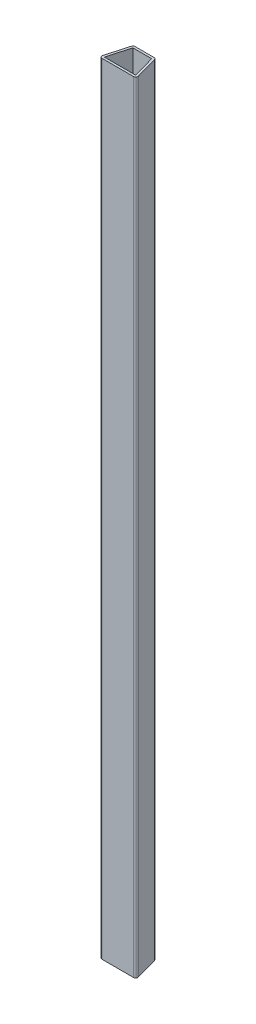
SolidWorks part; units mm, degrees
ref_plane "Front Plane" through (0, 0, 0) normal (0, 0, 1) x (1, 0, 0)
ref_plane "Top Plane" through (0, 0, 0) normal (0, 1, 0) x (1, 0, 0)
ref_plane "Right Plane" through (0, 0, 0) normal (1, 0, 0) x (0, 0, -1)
sketch "Sketch1" plane through (0, 0, 0) normal (0, 1, 0) x (1, 0, 0)
  line L8 (-7.0399, -6) -> (7.0399, -6)
  line L9 (5.19, 5.2707) -> (8.0025, -4.7293)
  line L10 (-4.2274, 6) -> (4.2274, 6)
  line L11 (-5.19, 5.2707) -> (-8.0025, -4.7293)
  line L12 (-7.0399, -5) -> (7.0399, -5)
  line L13 (4.2274, 5) -> (7.0399, -5)
  line L14 (-4.2274, 5) -> (4.2274, 5)
  line L15 (-4.2274, 5) -> (-7.0399, -5)
  arc A8 (5.19, 5.2707) -> (4.2274, 6) centre (4.2274, 5) ccw
  arc A9 (-4.2274, 6) -> (-5.19, 5.2707) centre (-4.2274, 5) ccw
  arc A10 (7.0399, -5) -> (7.0399, -5) centre (7.0399, -5) cw
  arc A11 (8.0025, -4.7293) -> (7.0399, -6) centre (7.0399, -5) cw
  arc A12 (-8.0025, -4.7293) -> (-7.0399, -6) centre (-7.0399, -5) ccw
  arc A13 (4.2274, 5) -> (4.2274, 5) centre (4.2274, 5) ccw
  arc A14 (-4.2274, 5) -> (-4.2274, 5) centre (-4.2274, 5) ccw
  arc A15 (-7.0399, -5) -> (-7.0399, -5) centre (-7.0399, -5) ccw
  dimension "D2" = 1
  dimension "D1" = 1
extrude "Boss-Extrude1" add sketch "Sketch1" along normal blind 350
